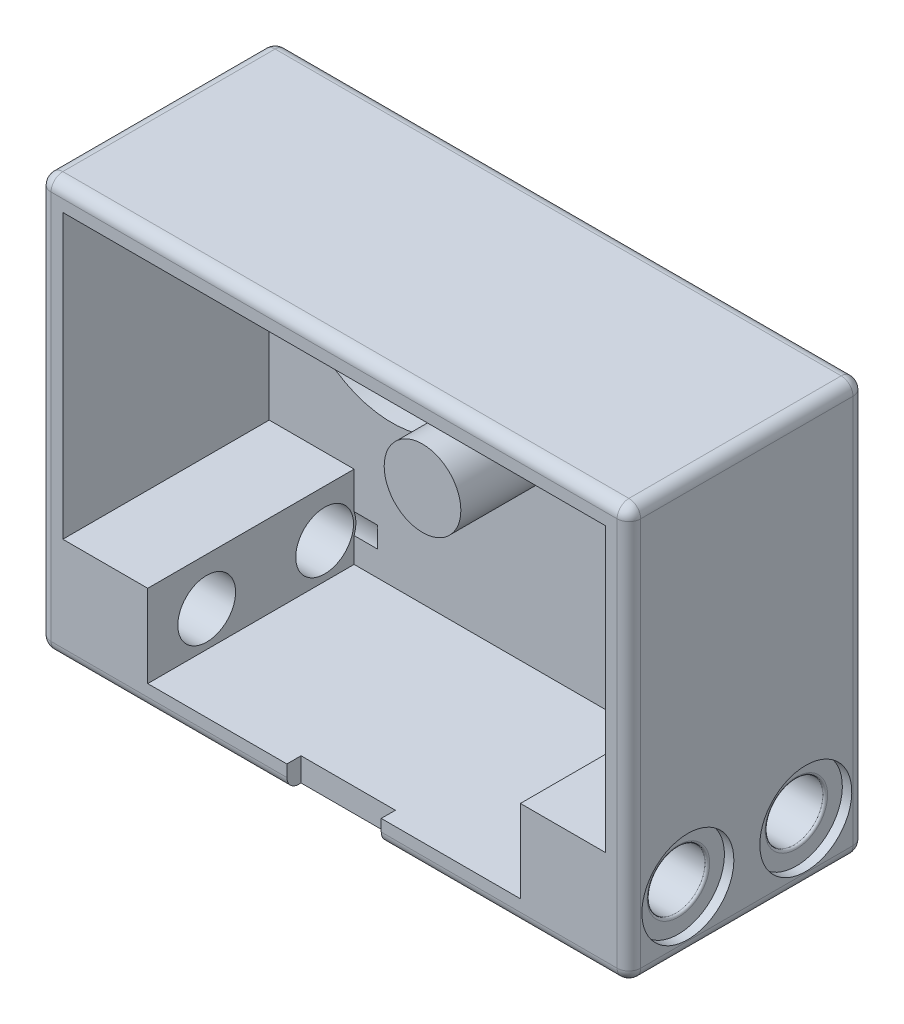
SolidWorks part; units mm, degrees
ref_plane "Front Plane" through (0, 0, 0) normal (0, 0, 1) x (1, 0, 0)
ref_plane "Top Plane" through (0, 0, 0) normal (0, 1, 0) x (1, 0, 0)
ref_plane "Right Plane" through (0, 0, 0) normal (1, 0, 0) x (0, 0, -1)
sketch "Sketch1" plane through (0, 0, 0) normal (0, 0, 1) x (1, 0, 0)
  line L0 (-25, 4.9) -> (25, 4.9) construction
  line L1 (-25, -17.5) -> (25, -17.5)
  line L2 (-25, -17.5) -> (-25, 17.5)
  line L3 (-25, 17.5) -> (25, 17.5)
  line L4 (25, -17.5) -> (25, 17.5)
  line L5 (-25, -17.5) -> (25, 17.5) construction
  line L6 (-25, 17.5) -> (25, -17.5) construction
  line L7 (-12.6, 4.9) -> (0, 17.5) construction
  line L8 (0, 17.5) -> (12.6, 4.9) construction
  circle A0 centre (-12.6, 4.9) radius 8.4
  circle A1 centre (12.6, 4.9) radius 8.4
  point P0 (0, 0)
  dimension "D3" = 16.8
  dimension "D4" = 42
  dimension "D1" = 50
  dimension "D2" = 35
  dimension "D5" = 4.2
extrude "Boss-Extrude1" add sketch "Sketch1" along normal blind 2.5
sketch "Sketch2" plane through (0, 0, 2.5) normal (0, 0, 1) x (1, 0, 0)
  line L0 (23, 15.5) -> (-23, 15.5)
  line L1 (-23, 15.5) -> (-23, -15.5)
  line L2 (-23, -15.5) -> (23, -15.5)
  line L3 (23, -15.5) -> (23, 15.5)
  line L4 (25, -17.5) -> (25, 17.5)
  line L5 (25, 17.5) -> (-25, 17.5)
  line L6 (-25, 17.5) -> (-25, -17.5)
  line L7 (-25, -17.5) -> (25, -17.5)
  line L8 (25, -17.5) -> (25, 17.5)
  line L9 (25, 17.5) -> (-25, 17.5)
  line L10 (-25, 17.5) -> (-25, -17.5)
  line L11 (-25, -17.5) -> (25, -17.5)
  dimension "D1" = 0
  dimension "D2" = 2
extrude "Boss-Extrude2" add sketch "Sketch2" along normal blind 17.5
sketch "Sketch3" plane through (0, 0, 2.5) normal (0, 0, 1) x (1, 0, 0)
  line L0 (0, 2.9945) -> (0, 17.5) construction
  line L1 (25, 17.5) -> (-25, 17.5) construction
  circle A0 centre (0, 2.9945) radius 3.25
  point P6 (0, 0)
  point P7 (0, 2.9945)
  dimension "D1" = 6.5
extrude "Boss-Extrude3" add sketch "Sketch3" along normal blind 10
sketch "Sketch5" plane through (25, 0, 0) normal (1, 0, 0) x (0, 0, -1)
  line L0 (0, -17.5) -> (0, 17.5) construction
  line L1 (-20, -17.5) -> (0, -17.5)
  line L2 (-20, -17.5) -> (-20, -8.5)
  line L3 (-20, -8.5) -> (0, -8.5)
  line L4 (0, -17.5) -> (0, -8.5)
  line L5 (-20, 17.5) -> (0, 17.5) construction
  dimension "D1" = 26
sketch "Sketch4" plane through (25, 0, 0) normal (1, 0, 0) x (0, 0, -1)
  line L0 (0, -12.5) -> (-20, -12.5) construction
  line L1 (0, -17.5) -> (0, 17.5) construction
  line L2 (-20, -17.5) -> (-20, 17.5) construction
  line L3 (-5, -17.5) -> (-5, 17.5) construction
  line L4 (-20, -17.5) -> (0, -17.5) construction
  line L5 (-20, 17.5) -> (0, 17.5) construction
  circle A0 centre (-5, -12.5) radius 2.45
  circle A1 centre (-15, -12.5) radius 2.45
  dimension "D3" = 4.9
  dimension "D4" = 10
  dimension "D1" = 5
  dimension "D2" = 5
extrude "Boss-Extrude4" add sketch "Sketch5" against normal blind 9.2
extrude "Cut-Extrude1" cut sketch "Sketch4" against normal blind 9.2
sketch "Sketch6" plane through (15.8, 0, 0) normal (-1, 0, 0) x (0, 0, 1)
  circle A0 centre (5, -12.5) radius 2.65
  circle A1 centre (5, -12.5) radius 2.45 construction
  dimension "D1" = 0.2
extrude "Cut-Extrude2" cut sketch "Sketch6" along normal blind 2
sketch "Sketch7" plane through (25, 0, 0) normal (1, 0, 0) x (0, 0, -1)
  circle A0 centre (-15, -12.5) radius 3.9
  circle A1 centre (-5, -12.5) radius 3.9
  dimension "D1" = 7.8
extrude "Cut-Extrude3" cut sketch "Sketch7" against normal blind 0.8
fillet "Fillet1" radius 0.2 2 edges at (24.2, -10.05, 5) (24.2, -10.05, 15)
mirror "Mirror1" about plane through (0, 0, 0) normal (1, 0, 0) of "Fillet1", "Cut-Extrude3", "Cut-Extrude2", "Cut-Extrude1", "Boss-Extrude4"
fillet "Fillet2" radius 1 14 edges at (25, 0, 20) (0, -17.5, 20) (-25, 0, 20) (0, 17.5, 20) (21, 4.9, 0) (-4.2, 4.9, 0) (-25, 0, 0) (0, 17.5, 0) (0, -17.5, 0) (25, 0, 0) (25, -17.5, 10) (-25, -17.5, 10) (25, 17.5, 10) (-25, 17.5, 10)
sketch "Sketch8" plane through (0, -17.5, 0) normal (0, -1, 0) x (1, 0, 0)
  line L0 (-24, 20) -> (24, 20) construction
  line L1 (-4, 21.2) -> (4, 21.2)
  line L2 (-4, 21.2) -> (-4, 18.8)
  line L3 (-4, 18.8) -> (4, 18.8)
  line L4 (4, 21.2) -> (4, 18.8)
  line L5 (-4, 21.2) -> (4, 18.8) construction
  line L6 (-4, 18.8) -> (4, 21.2) construction
  point P0 (0, 20)
  dimension "D1" = 8
  dimension "D2" = 1.2
extrude "Cut-Extrude4" cut sketch "Sketch8" against normal blind 6.8
